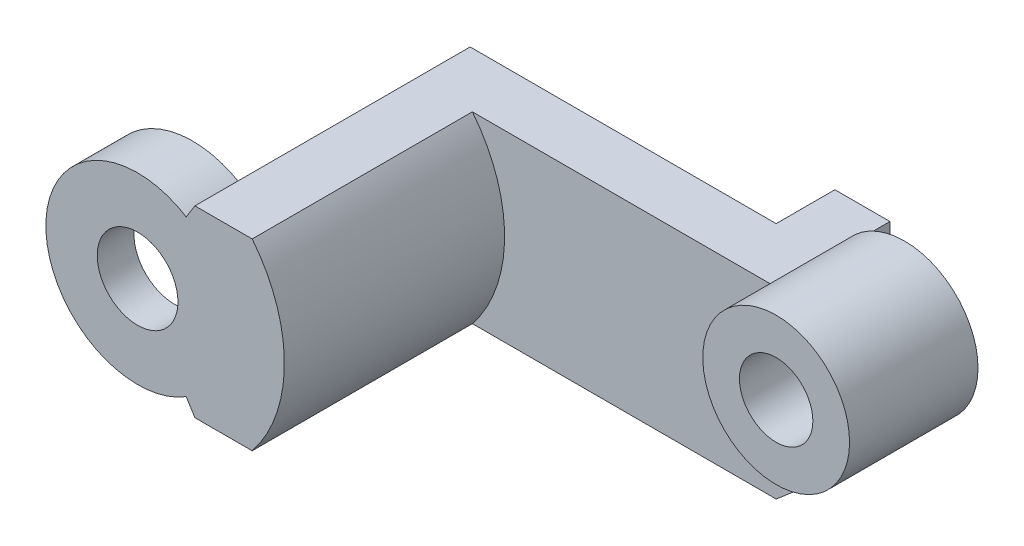
SolidWorks part; units mm, degrees
ref_plane "Front Plane" through (0, 0, 0) normal (0, 0, 1) x (1, 0, 0)
ref_plane "Top Plane" through (0, 0, 0) normal (0, 1, 0) x (1, 0, 0)
ref_plane "Right Plane" through (0, 0, 0) normal (1, 0, 0) x (0, 0, -1)
sketch "Sketch1" plane through (0, 0, 0) normal (0, 0, 1) x (1, 0, 0)
  circle A0 centre (0, 0) radius 2.5
  circle A1 centre (0, 0) radius 1.1
  dimension "D1" = 2.2
  dimension "D2" = 5
extrude "Boss-Extrude1" add sketch "Sketch1" against normal blind 1
sketch "Sketch2" plane through (0, 0, -1) normal (0, 0, 1) x (1, 0, 0)
  circle A0 centre (0, 0) radius 2.05
  circle A2 centre (0, 0) radius 2.5
  circle A3 centre (0, 0) radius 2.5
  dimension "D2" = 4.1
  dimension "D1" = 0
extrude "Boss-Extrude2" add sketch "Sketch2" against normal blind 0.5
sketch "Sketch3" plane through (0, 0, 0) normal (0, 0, 1) x (1, 0, 0)
  line L0 (0, -2.5) -> (3.1225, -2.5) construction
  line L1 (0, 2.5) -> (3.1225, 2.5) construction
  line L2 (1.5612, -2.5) -> (0, 0) construction
  line L3 (0, 0) -> (1.5612, 2.5) construction
  line L4 (3.1225, -2.5) -> (1.5612, -2.5)
  line L5 (1.5612, -2.5) -> (1.3242, -2.1205)
  line L6 (3.1225, 2.5) -> (1.5612, 2.5)
  line L7 (1.5612, 2.5) -> (1.3242, 2.1205)
  arc A0 (3.1225, -2.5) -> (3.1225, 2.5) centre (0, 0) ccw
  circle A1 centre (0, 0) radius 2.5 construction
  arc A2 (0, 2.5) -> (0, -2.5) centre (0, 0) ccw construction
  arc A3 (1.3242, -2.1205) -> (1.3242, 2.1205) centre (0, 0) ccw
  dimension "D1" = 4
extrude "Boss-Extrude4" add sketch "Sketch3" against normal blind 7.5
sketch "Sketch5" plane through (0, 0, -7.5) normal (0, 0, -1) x (-1, 0, 0)
  line L0 (0, 0) -> (-13.4, 0) construction
  line L1 (-3.1225, -2.5) -> (-11.4, -2.5)
  line L2 (-3.1225, -2.5) -> (-3.1225, 2.5)
  line L3 (-3.1225, 2.5) -> (-11.512, 2.5)
  line L5 (-13.4, 0) -> (-13.4, 1.84) construction
  line L6 (-14.6993, 0.3196) -> (-11.4, -2.5)
  circle A0 centre (-13.4, 1.84) radius 1
  arc A1 (-11.512, 2.5) -> (-14.6993, 0.3196) centre (-13.4, 1.84) ccw
  dimension "D3" = 2
  dimension "D4" = 2
  dimension "D1" = 13.4
  dimension "D2" = 1.84
  dimension "D5" = 2
extrude "Boss-Extrude5" add sketch "Sketch5" against normal blind 1.5
sketch "Sketch6" plane through (0, 0, -7.5) normal (0, 0, -1) x (-1, 0, 0)
  line L0 (-11.512, 2.5) -> (-1.5612, 2.5) construction
  line L1 (-11.4, -2.5) -> (-9.9, -2.5)
  line L2 (-11.4, -2.5) -> (-11.4, 2.5)
  line L3 (-11.4, 2.5) -> (-9.9, 2.5)
  line L4 (-9.9, -2.5) -> (-9.9, 2.5)
  dimension "D1" = 1.5
extrude "Boss-Extrude6" add sketch "Sketch6" along normal blind 1.6
sketch "Sketch7" plane through (0, 0, -6) normal (0, 0, 1) x (1, 0, 0)
  circle A0 centre (13.4, 1.84) radius 1 construction
  circle A1 centre (13.4, 1.84) radius 1
  circle A2 centre (13.4, 1.84) radius 2
  arc A4 (14.6993, 0.3196) -> (11.512, 2.5) centre (13.4, 1.84) ccw construction
extrude "Boss-Extrude7" add sketch "Sketch7" along normal blind 2
